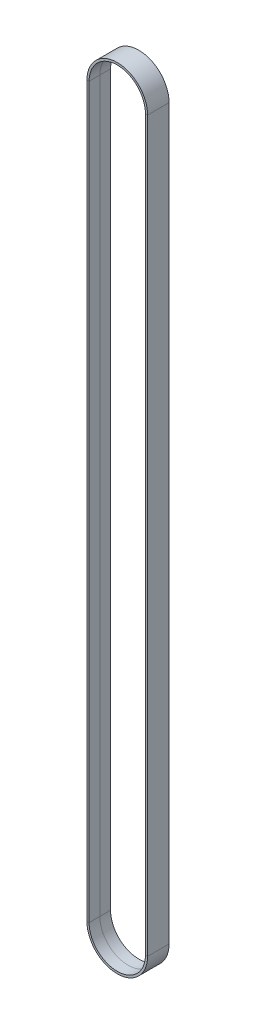
SolidWorks part; units mm, degrees
ref_plane "Спереди" through (0, 0, 0) normal (0, 0, 1) x (1, 0, 0)
ref_plane "Сверху" through (0, 0, 0) normal (0, 1, 0) x (1, 0, 0)
ref_plane "Справа" through (0, 0, 0) normal (1, 0, 0) x (0, 0, -1)
sketch "Эскиз2" plane through (0, 0, 0) normal (0, 0, 1) x (1, 0, 0)
  line L0 (0, 0) -> (1, 0) construction
  line L1 (0, 0) -> (0, 1) construction
  line L2 (26.25, 0) -> (26.25, -678.6787)
  line L3 (-26.25, -678.6787) -> (-26.25, 0)
  arc A0 (-26.25, 0) -> (26.25, 0) centre (0, 0) cw
  arc A1 (26.25, -678.6787) -> (-26.25, -678.6787) centre (0, -678.6787) cw
ref_plane "Плоскость1" through (0, 0, 0) normal (0, 0, 1) x (1, 0, 0)
sketch "Эскиз3" plane through (0, 0, 0) normal (0, 0, 1) x (1, 0, 0)
  line L0 (-26.25, -678.6787) -> (-26.25, 0) construction
  line L1 (26.25, 0) -> (26.25, -678.6787) construction
  line L2 (-26.25, -678.6787) -> (-26.25, 0)
  line L3 (26.25, 0) -> (26.25, -678.6787)
  arc A0 (-26.25, -678.6787) -> (26.25, -678.6787) centre (0, -678.6787) ccw construction
  arc A1 (26.25, 0) -> (-26.25, 0) centre (0, 0) ccw construction
  arc A2 (-26.25, -678.6787) -> (26.25, -678.6787) centre (0, -678.6787) ccw
  arc A3 (26.25, 0) -> (-26.25, 0) centre (0, 0) ccw
ref_plane "Плоскость2" through (0, 0, 0) normal (0, 1, 0) x (1, 0, 0)
sketch "Эскиз4" plane through (0, 0, 0) normal (0, 1, 0) x (1, 0, 0)
  line L0 (1.6245, -10) -> (0.6065, -10) construction
  line L2 (26.25, 0) -> (26.25, -10)
  line L3 (26.25, -10) -> (28.25, -10)
  line L5 (0.6065, 10) -> (1.6245, 10) construction
  line L7 (26.25, 0) -> (26.25, 10)
  line L8 (26.25, 10) -> (28.25, 10)
  line L10 (28.25, 10) -> (28.25, -10)
  dimension "D1" = 2
  dimension "D2" = 2
sweep "По траектории1" add profiles "Эскиз4" path "Эскиз3"
